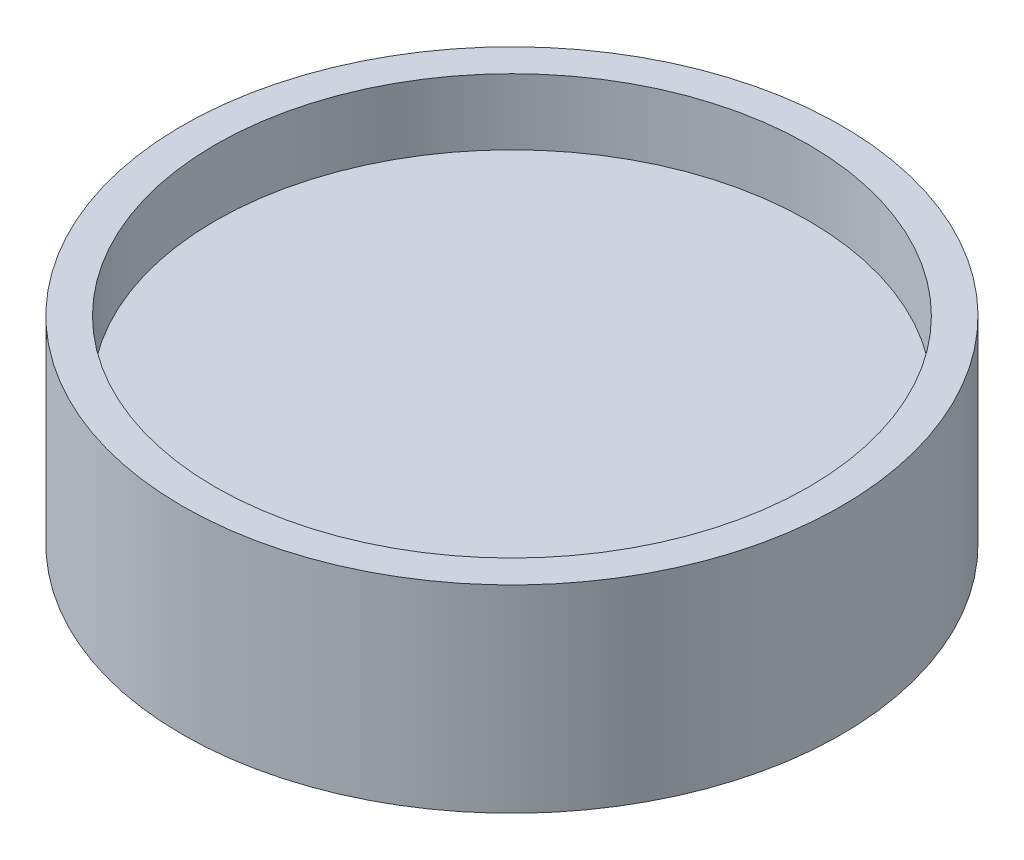
SolidWorks part; units mm, degrees
material "Pine"
ref_plane "Front Plane" through (0, 0, 0) normal (0, 0, 1) x (1, 0, 0)
ref_plane "Top Plane" through (0, 0, 0) normal (0, 1, 0) x (1, 0, 0)
ref_plane "Right Plane" through (0, 0, 0) normal (1, 0, 0) x (0, 0, -1)
sketch "Sketch3" plane through (0, 0, 0) normal (0, 1, 0) x (1, 0, 0)
  circle A0 centre (0, 0) radius 50
  dimension "D1" = 100
extrude "Boss-Extrude1" add sketch "Sketch3" along normal blind 30
sketch "Sketch4" plane through (0, 30, 0) normal (0, 1, 0) x (1, 0, 0)
  circle A3 centre (0, 0) radius 45
  circle A4 centre (0, 0) radius 45
  dimension "D1" = 5
extrude "Cut-Extrude1" cut sketch "Sketch4" against normal blind 10
sketch "Sketch5" plane through (0, 0, 0) normal (0, -1, 0) x (1, 0, 0)
  circle A2 centre (0, 0) radius 45
  circle A3 centre (0, 0) radius 45
  dimension "D1" = 5
extrude "Cut-Extrude2" cut sketch "Sketch5" against normal blind 19
